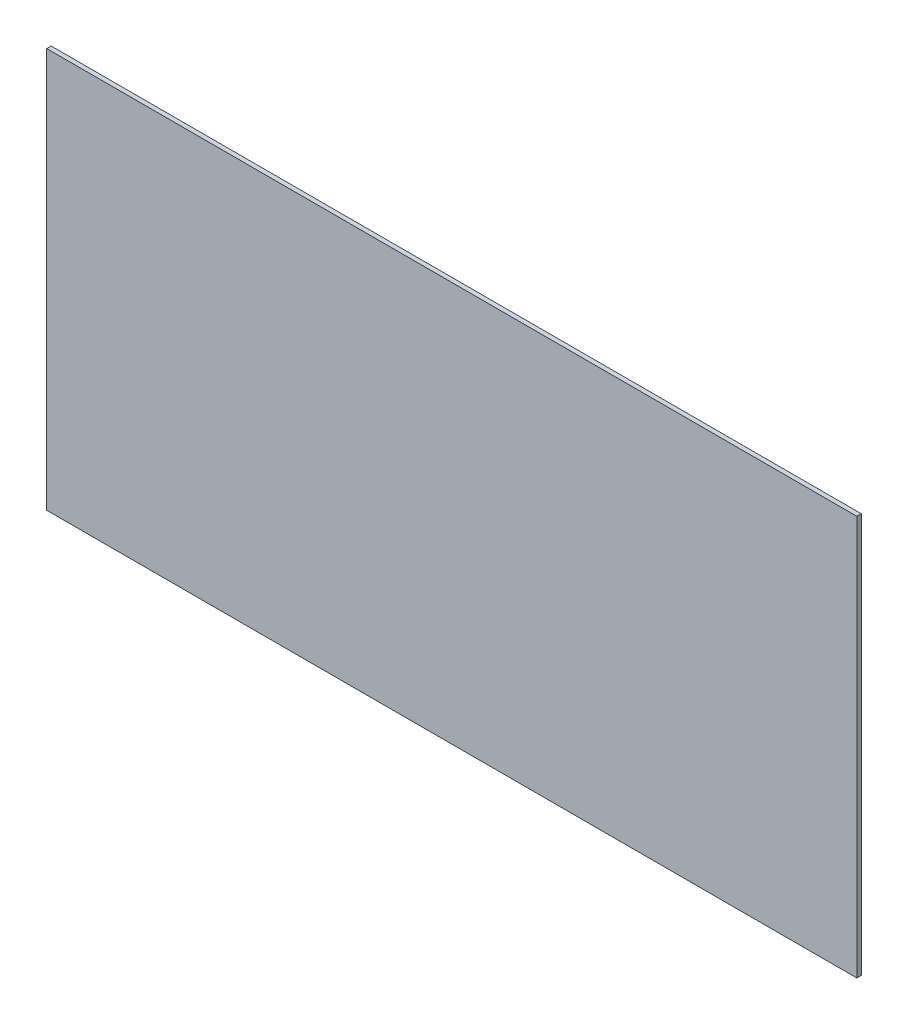
SolidWorks part; units mm, degrees
ref_plane "Front Plane" through (0, 0, 0) normal (0, 0, 1) x (1, 0, 0)
ref_plane "Top Plane" through (0, 0, 0) normal (0, 1, 0) x (1, 0, 0)
ref_plane "Right Plane" through (0, 0, 0) normal (1, 0, 0) x (0, 0, -1)
sketch "Sketch1" plane through (0, 0, 0) normal (0, 0, 1) x (1, 0, 0)
  line L1 (-273.5, -135) -> (273.5, -135)
  line L2 (-273.5, -135) -> (-273.5, 135)
  line L3 (-273.5, 135) -> (273.5, 135)
  line L4 (273.5, -135) -> (273.5, 135)
  line L5 (-273.5, -135) -> (273.5, 135) construction
  line L6 (-273.5, 135) -> (273.5, -135) construction
  point P0 (0, 0)
  dimension "D1" = 270
  dimension "D2" = 547
extrude "Boss-Extrude1" add sketch "Sketch1" along normal blind 3
